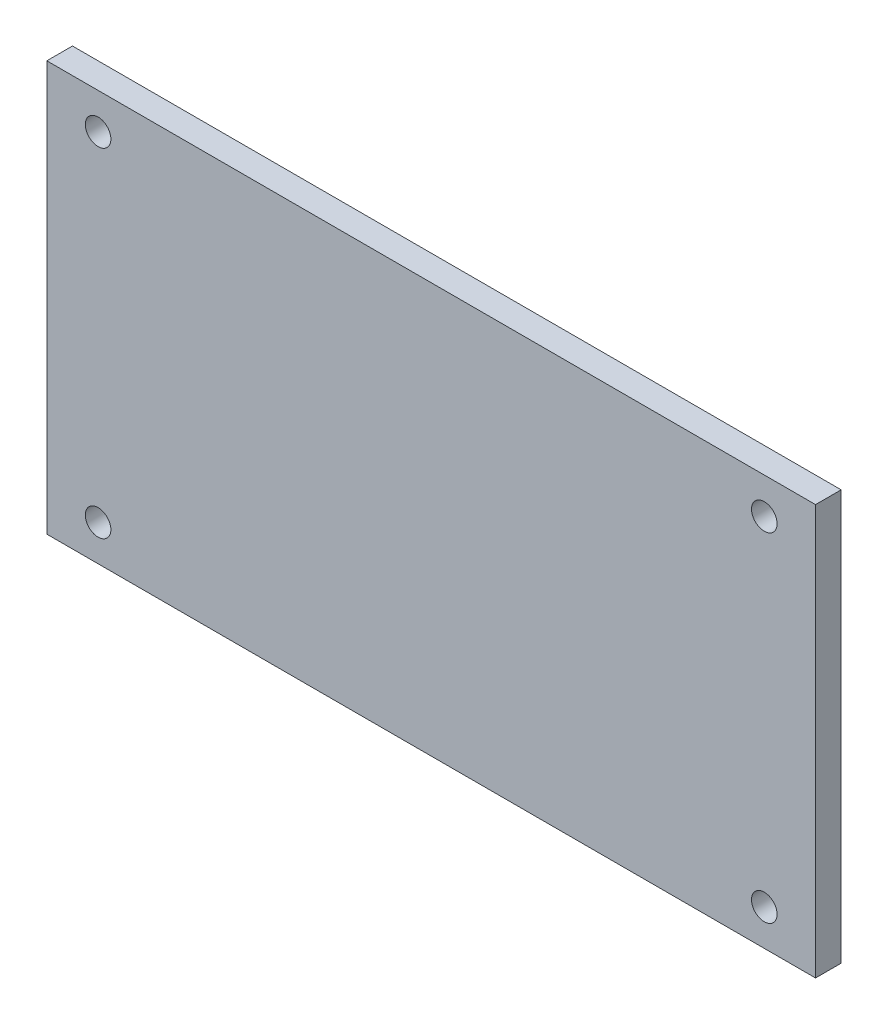
SolidWorks part; units mm, degrees
ref_plane "Front Plane" through (0, 0, 0) normal (0, 0, 1) x (1, 0, 0)
ref_plane "Top Plane" through (0, 0, 0) normal (0, 1, 0) x (1, 0, 0)
ref_plane "Right Plane" through (0, 0, 0) normal (1, 0, 0) x (0, 0, -1)
sketch "Sketch1" plane through (0, 0, 0) normal (0, 0, 1) x (1, 0, 0)
  line L0 (0, 50) -> (0, -30) construction
  line L1 (-75, 50) -> (75, 50)
  line L2 (-75, 50) -> (-75, -30)
  line L3 (-75, -30) -> (75, -30)
  line L4 (75, 50) -> (75, -30)
  line L7 (-75, 10) -> (75, 10) construction
  circle A0 centre (-65, 43) radius 2.5
  circle A1 centre (65, 43) radius 2.5
  circle A2 centre (65, -23) radius 2.5
  circle A3 centre (-65, -23) radius 2.5
  point P0 (0, 0)
  dimension "D3" = 10
  dimension "D4" = 7
  dimension "D1" = 150
  dimension "D2" = 80
extrude "Boss-Extrude1" add sketch "Sketch1" along normal blind 5
